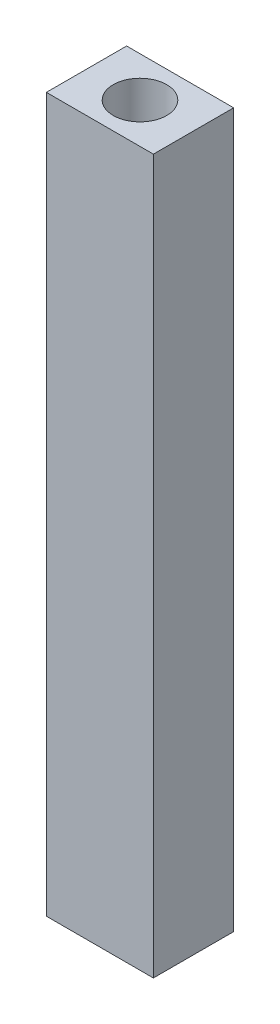
SolidWorks part; units mm, degrees
ref_plane "前视基准面" through (0, 0, 0) normal (0, 0, 1) x (1, 0, 0)
ref_plane "上视基准面" through (0, 0, 0) normal (0, 1, 0) x (1, 0, 0)
ref_plane "右视基准面" through (0, 0, 0) normal (1, 0, 0) x (0, 0, -1)
other "Configuration Table"
sketch "草图2" plane through (0, 0, 0) normal (0, 1, 0) x (1, 0, 0)
  line L1 (-6, -4.5) -> (6, -4.5)
  line L2 (-6, -4.5) -> (-6, 4.5)
  line L3 (-6, 4.5) -> (6, 4.5)
  line L4 (6, -4.5) -> (6, 4.5)
  line L5 (-6, -4.5) -> (6, 4.5) construction
  line L6 (-6, 4.5) -> (6, -4.5) construction
  point P0 (0, 0)
  dimension "D1" = 12
  dimension "D2" = 9
extrude "凸台-拉伸1" add sketch "草图2" along normal blind 80
sketch "草图3" plane through (0, 0, 0) normal (0, -1, 0) x (1, 0, 0)
  circle A0 centre (0, 0) radius 3
  dimension "D1" = 6
extrude "切除-拉伸1" cut sketch "草图3" against normal blind 20
sketch "草图4" plane through (0, 80, 0) normal (0, 1, 0) x (1, 0, 0)
  circle A0 centre (0, 0) radius 3
  dimension "D1" = 6
extrude "切除-拉伸2" cut sketch "草图4" against normal blind 20
